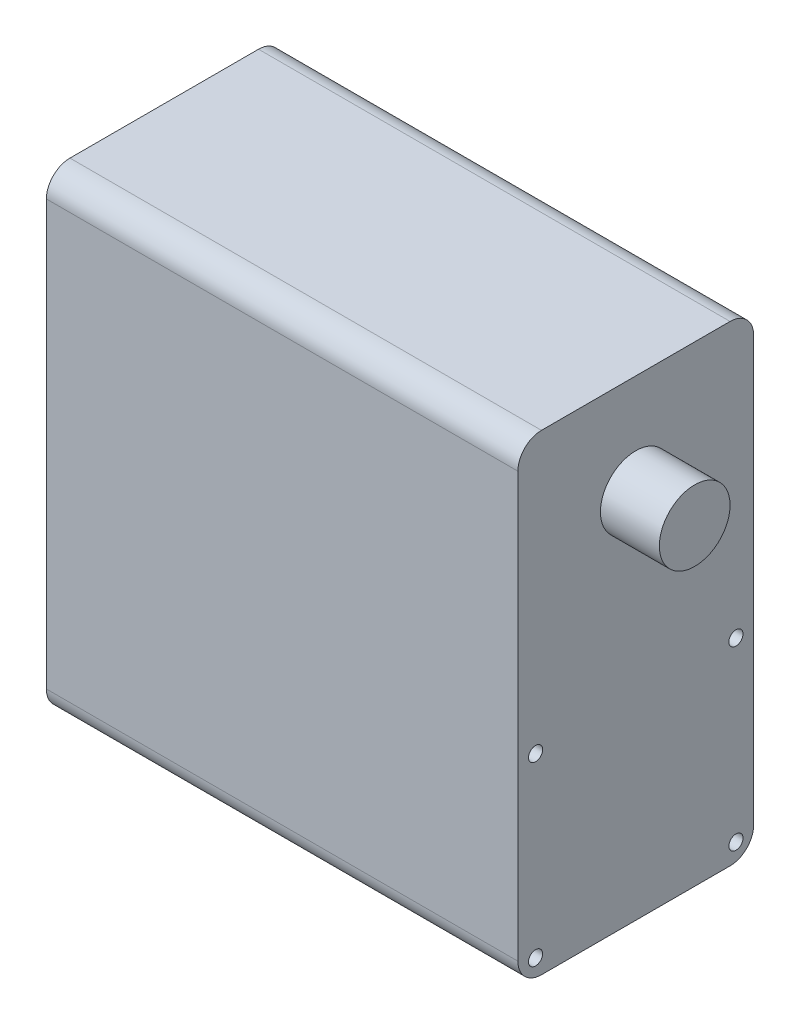
SolidWorks part; units mm, degrees
ref_plane "正面" through (0, 0, 0) normal (0, 0, 1) x (1, 0, 0)
ref_plane "平面" through (0, 0, 0) normal (0, 1, 0) x (1, 0, 0)
ref_plane "右側面" through (0, 0, 0) normal (1, 0, 0) x (0, 0, -1)
sketch "ｽｹｯﾁ1" plane through (0, 0, 0) normal (1, 0, 0) x (0, 0, -1)
  line L1 (8.409, 19.7991) -> (28.409, 19.7991)
  line L2 (8.409, 19.7991) -> (8.409, -20.2009)
  line L3 (8.409, -20.2009) -> (28.409, -20.2009)
  line L4 (28.409, 19.7991) -> (28.409, -20.2009)
extrude "ﾎﾞｽ - 押し出し1" add sketch "ｽｹｯﾁ1" along normal blind 40
sketch "ｽｹｯﾁ2" plane through (40, 0, 0) normal (1, 0, 0) x (0, 0, -1)
  line L1 (8.409, -20.2009) -> (28.409, -20.2009) construction
  line L2 (18.409, -20.2009) -> (18.409, -24.7228)
  circle A0 centre (26.909, -18.7009) radius 0.6
  circle A1 centre (26.909, -3.7009) radius 0.6
  circle A2 centre (9.909, -3.7009) radius 0.6
  circle A3 centre (9.909, -18.7009) radius 0.6
extrude "ｶｯﾄ - 押し出し1" cut sketch "ｽｹｯﾁ2" against normal blind 5 contours A0 | A1 | A2 | A3
sketch "ｽｹｯﾁ3" plane through (40, 0, 0) normal (1, 0, 0) x (0, 0, -1)
  line L0 (18.409, 19.7991) -> (18.409, 11.2991)
  line L1 (28.409, 19.7991) -> (8.409, 19.7991) construction
  circle A0 centre (18.409, 11.2991) radius 3
extrude "ﾎﾞｽ - 押し出し3" add sketch "ｽｹｯﾁ3" along normal blind 5 and the other way blind 45
sketch "ｽｹｯﾁ4" plane through (0, 0, 0) normal (-1, 0, 0) x (0, 0, 1)
  line L0 (-18.409, -17.2009) -> (-18.409, 3.417)
  circle A0 centre (-11.409, -13.7009) radius 1
  circle A1 centre (-11.409, -10.7009) radius 1
  circle A2 centre (-18.409, -17.2009) radius 1
  circle A3 centre (-25.409, -10.7009) radius 1
  circle A4 centre (-25.409, -13.7009) radius 1
  circle A5 centre (-10.409, 2.2991) radius 1
  circle A6 centre (-26.409, 2.2991) radius 1
extrude "ｶｯﾄ - 押し出し2" cut sketch "ｽｹｯﾁ4" against normal blind 5 contours A0 | A4 | A6 | A5 | A1 | A3 | A2
fillet "ﾌｨﾚｯﾄ1" radius 2 4 edges at (20, -20.2009, -28.409) (20, -20.2009, -8.409) (20, 19.7991, -8.409) (20, 19.7991, -28.409)
